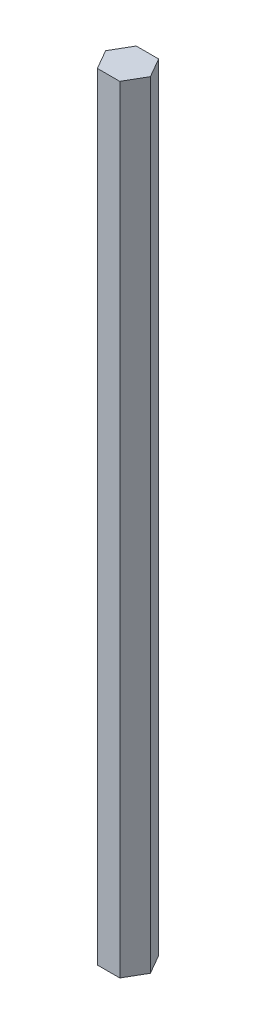
SolidWorks part; units mm, degrees
ref_plane "Front Plane" through (0, 0, 0) normal (0, 0, 1) x (1, 0, 0)
ref_plane "Top Plane" through (0, 0, 0) normal (0, 1, 0) x (1, 0, 0)
ref_plane "Right Plane" through (0, 0, 0) normal (1, 0, 0) x (0, 0, -1)
sketch "Sketch2" plane through (0, 0, 0) normal (0, 1, 0) x (1, 0, 0)
  line L1 (7.3323, 0) -> (3.6662, 6.35)
  line L2 (3.6662, 6.35) -> (-3.6662, 6.35)
  line L3 (-3.6662, 6.35) -> (-7.3323, 0)
  line L4 (-7.3323, 0) -> (-3.6662, -6.35)
  line L5 (-3.6662, -6.35) -> (3.6662, -6.35)
  line L6 (3.6662, -6.35) -> (7.3323, 0)
  circle A0 centre (0, 0) radius 6.35 construction
  dimension "D1" = 6.35
extrude "Boss-Extrude1" add sketch "Sketch2" along normal blind 254 contours L3 L4 L5 L6 L1 L2
